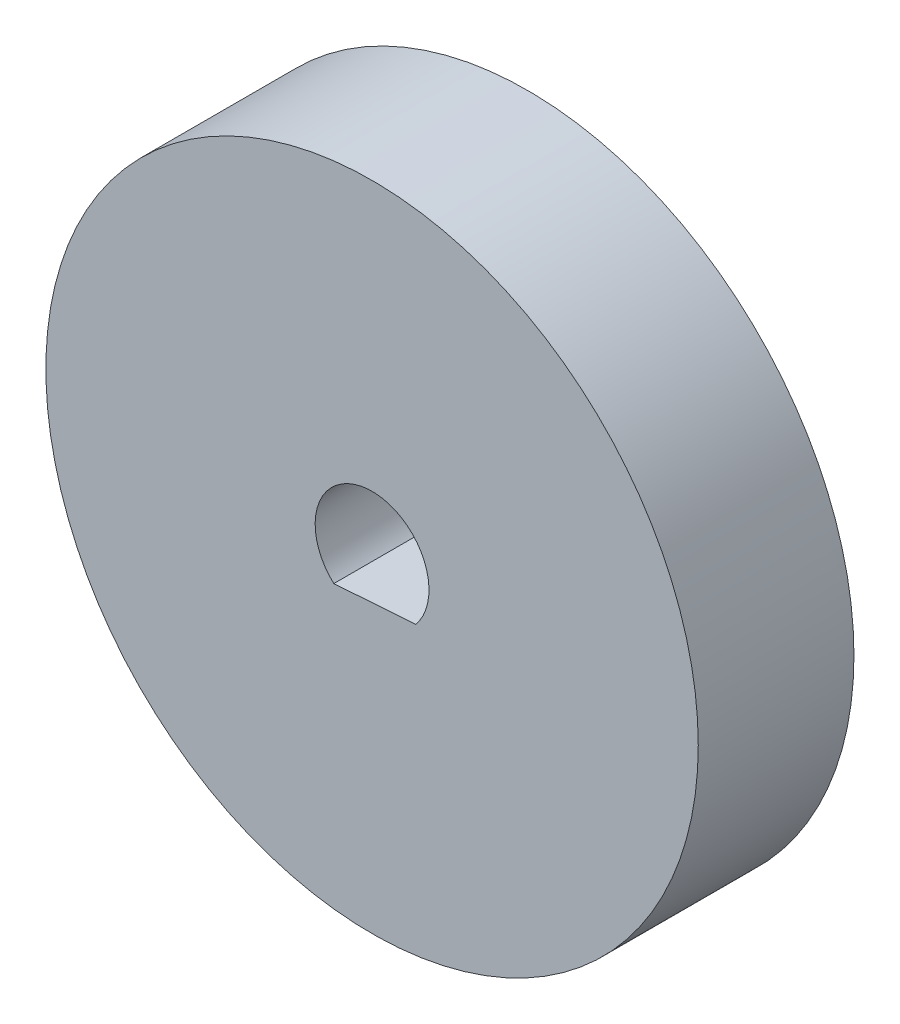
SolidWorks part; units mm, degrees
ref_plane "Front Plane" through (0, 0, 0) normal (0, 0, 1) x (1, 0, 0)
ref_plane "Top Plane" through (0, 0, 0) normal (0, 1, 0) x (1, 0, 0)
ref_plane "Right Plane" through (0, 0, 0) normal (1, 0, 0) x (0, 0, -1)
sketch "Sketch1" plane through (0, 0, 0) normal (0, 0, 1) x (1, 0, 0)
  circle A0 centre (0, 7.2896) radius 11.176
  dimension "D1" = 22.352
extrude "Boss-Extrude1" add sketch "Sketch1" along normal blind 5.334
sketch "Sketch2" plane through (0, 0, 0) normal (0, 0, -1) x (-1, 0, 0)
  line L1 (-1.4968, 6.0398) -> (1.3108, 5.8459)
  circle A0 centre (0, 7.2896) radius 1.95
  circle A1 centre (0, 7.2896) radius 11.176 construction
  dimension "D1" = 3.9
  dimension "D3" = 0
  dimension "D2" = 1.35
extrude "Cut-Extrude1" cut sketch "Sketch2" against normal through all contours L1 A0
equation "\"MDF\"= .21in"
equation "\"Foamcore\"= .13in"
equation "\"Gmaterial\"= \"MDF\""
equation "\"D1@Boss-Extrude1\"=\"MDF\""
